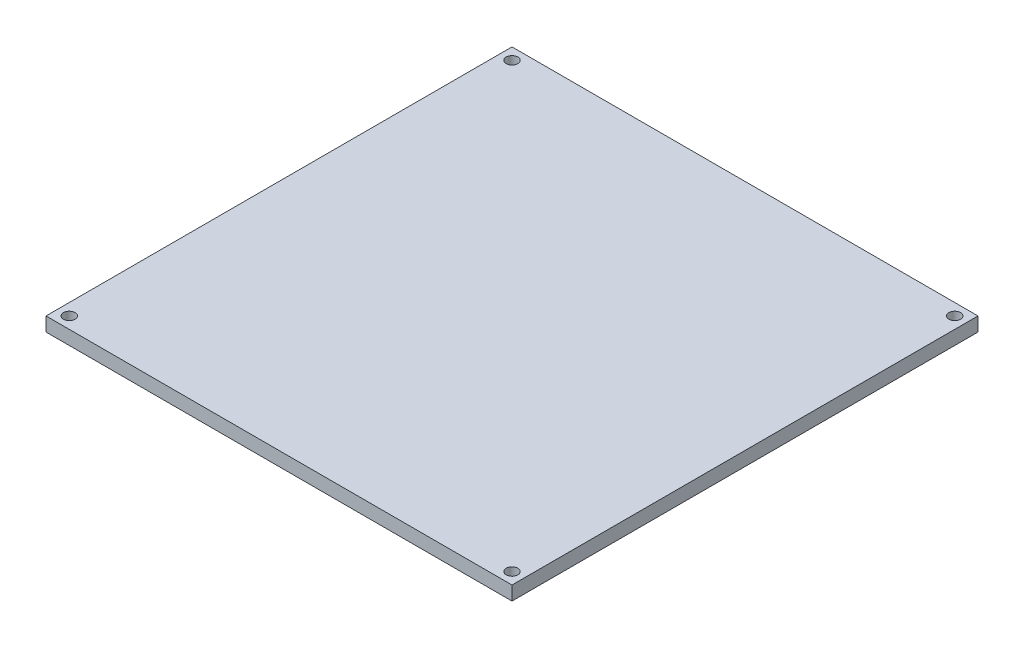
SolidWorks part; units mm, degrees
ref_plane "Front Plane" through (0, 0, 0) normal (0, 0, 1) x (1, 0, 0)
ref_plane "Top Plane" through (0, 0, 0) normal (0, 1, 0) x (1, 0, 0)
ref_plane "Right Plane" through (0, 0, 0) normal (1, 0, 0) x (0, 0, -1)
sketch "Sketch2" plane through (0, 0, 0) normal (0, 1, 0) x (1, 0, 0)
  line L0 (0, 0) -> (100, 0)
  line L1 (100, 0) -> (100, 100)
  line L2 (100, 100) -> (0, 100)
  line L3 (0, 100) -> (0, 0)
  circle A0 centre (2.5, 97.5) radius 1.25
  circle A1 centre (2.5, 2.5) radius 1.25
  circle A2 centre (97.5, 97.5) radius 1.25
  circle A3 centre (97.5, 2.5) radius 1.25
  dimension "D3" = 2.5
  dimension "D4" = 2.5
  dimension "D9" = 2.5
  dimension "D10" = 2.5
  dimension "D1" = 100
  dimension "D2" = 100
  dimension "D5" = 2.5
  dimension "D6" = 2.5
  dimension "D7" = 2.5
  dimension "D8" = 2.5
  dimension "D11" = 2.5
  dimension "D12" = 2.5
  dimension "D13" = 2.5
  dimension "D14" = 2.5
extrude "Boss-Extrude1" add sketch "Sketch2" along normal blind 3
